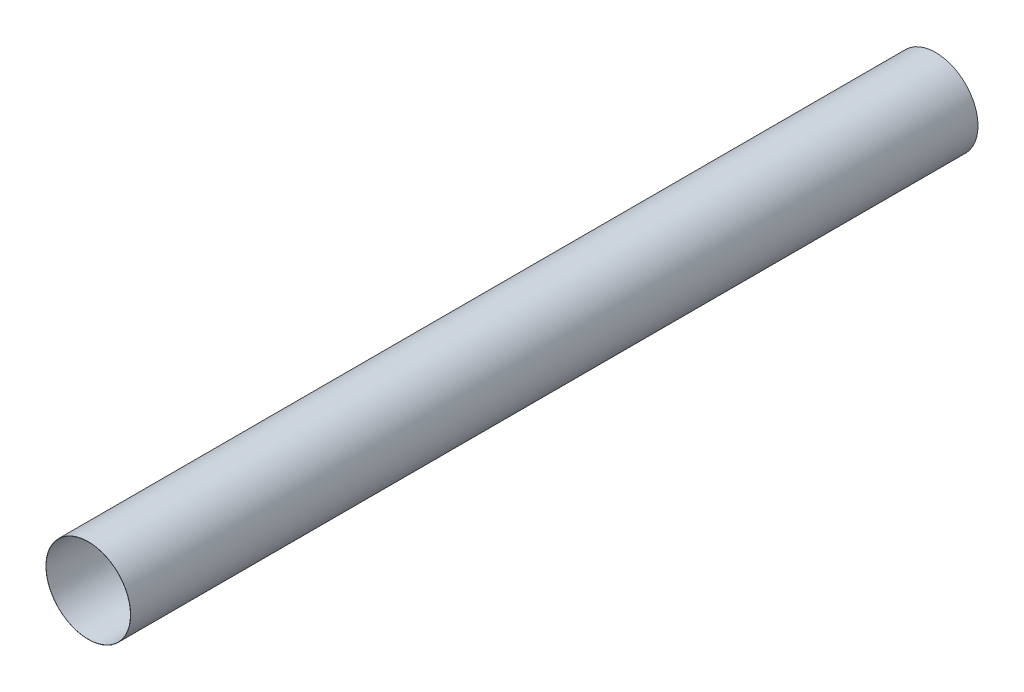
SolidWorks part; units mm, degrees
ref_plane "Front Plane" through (0, 0, 0) normal (0, 0, 1) x (1, 0, 0)
ref_plane "Top Plane" through (0, 0, 0) normal (0, 1, 0) x (1, 0, 0)
ref_plane "Right Plane" through (0, 0, 0) normal (1, 0, 0) x (0, 0, -1)
sketch "Sketch2" plane through (0, 0, 0) normal (0, 0, 1) x (1, 0, 0)
  circle A1 centre (0, 0) radius 500
  circle A2 centre (0, 0) radius 498
extrude "Boss-Extrude1" add sketch "Sketch2" along normal blind 10000
